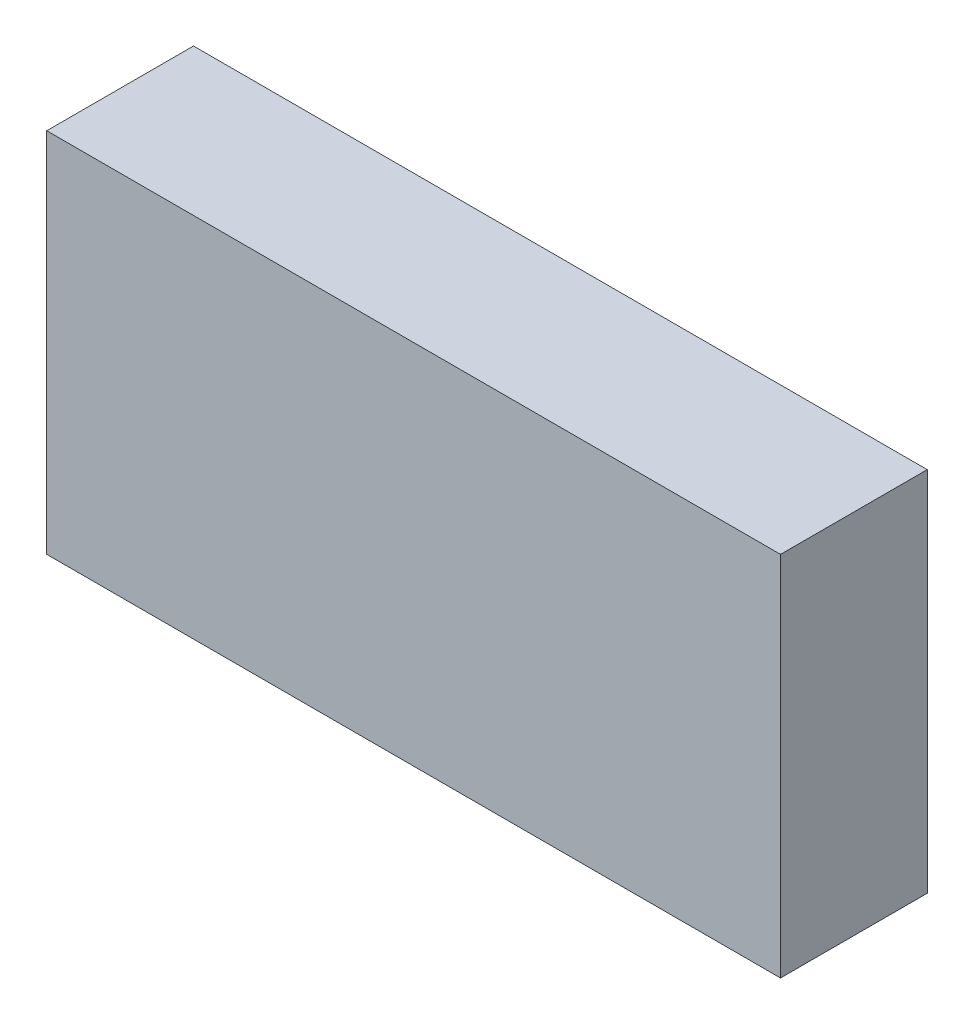
SolidWorks part; units mm, degrees
ref_plane "Plano frontal" through (0, 0, 0) normal (0, 0, 1) x (1, 0, 0)
ref_plane "Plano superior" through (0, 0, 0) normal (0, 1, 0) x (1, 0, 0)
ref_plane "Plano direito" through (0, 0, 0) normal (1, 0, 0) x (0, 0, -1)
sketch "Esboço1" plane through (0, 0, 0) normal (0, 0, 1) x (1, 0, 0)
  line L1 (30, -15) -> (-30, -15)
  line L2 (30, -15) -> (30, 15)
  line L3 (30, 15) -> (-30, 15)
  line L4 (-30, -15) -> (-30, 15)
  line L5 (30, -15) -> (-30, 15) construction
  line L6 (30, 15) -> (-30, -15) construction
  point P0 (0, 0)
  dimension "D1" = 60
  dimension "D2" = 30
extrude "Ressalto-extrusão1" add sketch "Esboço1" against normal blind 12
